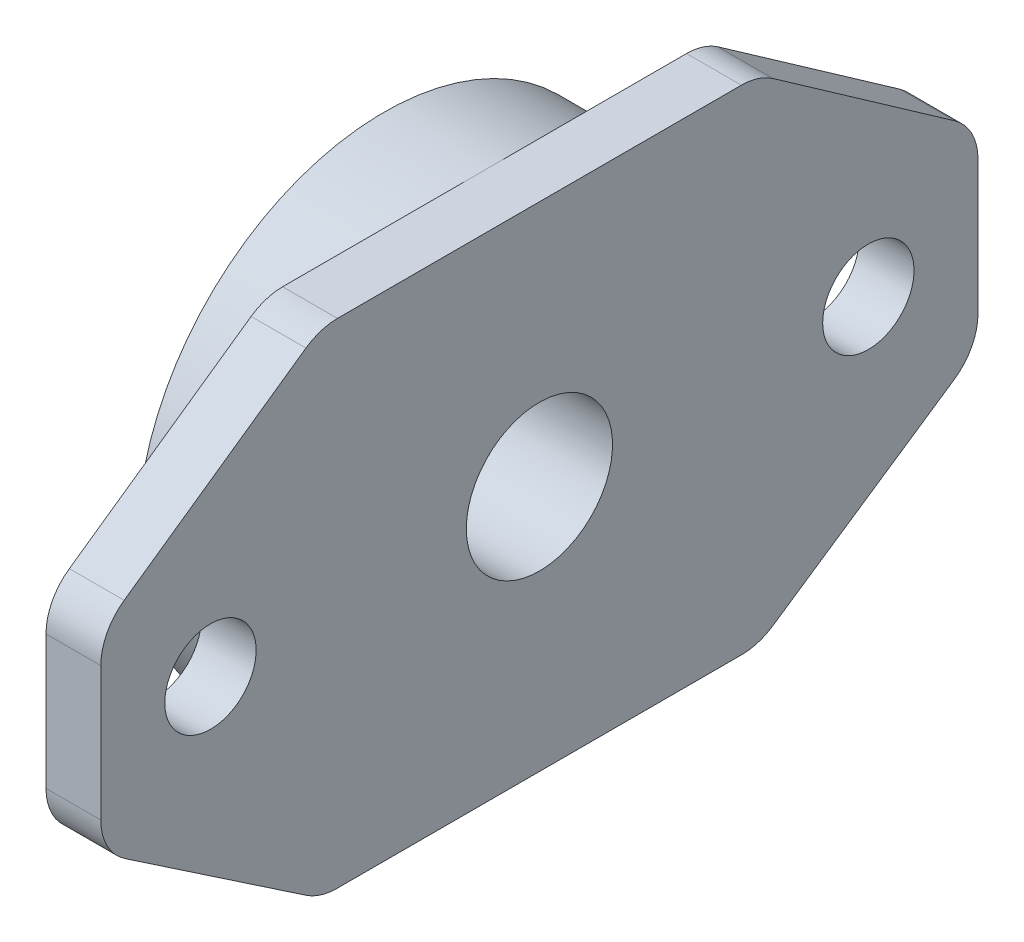
SolidWorks part; units mm, degrees
ref_plane "前视基准面" through (0, 0, 0) normal (0, 0, 1) x (1, 0, 0)
ref_plane "上视基准面" through (0, 0, 0) normal (0, 1, 0) x (1, 0, 0)
ref_plane "右视基准面" through (0, 0, 0) normal (1, 0, 0) x (0, 0, -1)
sketch "草图1" plane through (0, 0, 0) normal (1, 0, 0) x (0, 0, -1)
  line L1 (0, 0) -> (48, 0)
  line L2 (0, 0) -> (0, 27)
  line L3 (0, 27) -> (48, 27)
  line L4 (48, 0) -> (48, 27)
extrude "凸台-拉伸1" add sketch "草图1" along normal blind 3
sketch "草图5" plane through (0, 0, 0) normal (-1, 0, 0) x (0, 0, 1)
  line L0 (-48, 27) -> (0, 0) construction
  line L1 (0, 27) -> (-48, 0) construction
  circle A0 centre (-24, 13.5) radius 13.5
extrude "凸台-拉伸2" add sketch "草图5" along normal blind 5.5 contours A0
sketch "草图6" plane through (-5.5, 0, 0) normal (-1, 0, 0) x (0, 0, 1)
  circle A0 centre (-24, 13.5) radius 5
extrude "凸台-拉伸3" add sketch "草图6" along normal blind 4.5
sketch "草图7" plane through (-10, 0, 0) normal (-1, 0, 0) x (0, 0, 1)
  circle A2 centre (-24, 13.5) radius 4
  circle A3 centre (-24, 13.5) radius 4
  dimension "D1" = 1
extrude "切除-拉伸1" cut sketch "草图7" against normal through all
sketch "草图8" plane through (0, 0, 0) normal (-1, 0, 0) x (0, 0, 1)
  line L0 (-24, 13.5) -> (-42, 13.5) construction
  line L1 (-24, 13.5) -> (-6, 13.5) construction
  circle A0 centre (-42, 13.5) radius 2.5
  circle A1 centre (-6, 13.5) radius 2.5
extrude "切除-拉伸2" cut sketch "草图8" against normal through all
sketch "草图9" plane through (0, 0, 0) normal (-1, 0, 0) x (0, 0, 1)
  line L0 (-36, 27) -> (-48, 18.5808)
  line L1 (-48, 27) -> (-24, 27) construction
  line L2 (-48, 0) -> (-48, 27) construction
  line L3 (-36, 27) -> (-48, 27)
  line L4 (-48, 27) -> (-48, 18.5808)
  line L5 (-12, 27) -> (0, 18.5808)
  line L6 (-24, 27) -> (0, 27) construction
  line L7 (0, 27) -> (0, 0) construction
  line L8 (0, 18.5808) -> (0, 27)
  line L9 (0, 27) -> (-12, 27)
  line L10 (0, 0) -> (-12, 0)
  line L11 (0, 0) -> (-24, 0) construction
  line L12 (-12, 0) -> (0, 8.1065)
  line L13 (0, 8.1065) -> (0, 0)
  line L14 (-48, 0) -> (-48, 8.1065)
  line L15 (-48, 8.1065) -> (-36, 0)
  line L16 (-24, 0) -> (-48, 0) construction
  line L17 (-36, 0) -> (-48, 0)
extrude "切除-拉伸3" cut sketch "草图9" against normal through all
fillet "圆角1" radius 3 8 edges at (1.5, 0, -36) (1.5, 0, -12) (1.5, 8.1065, 0) (1.5, 18.5808, 0) (1.5, 27, -12) (1.5, 8.1065, -48) (1.5, 27, -36) (1.5, 18.5808, -48)
